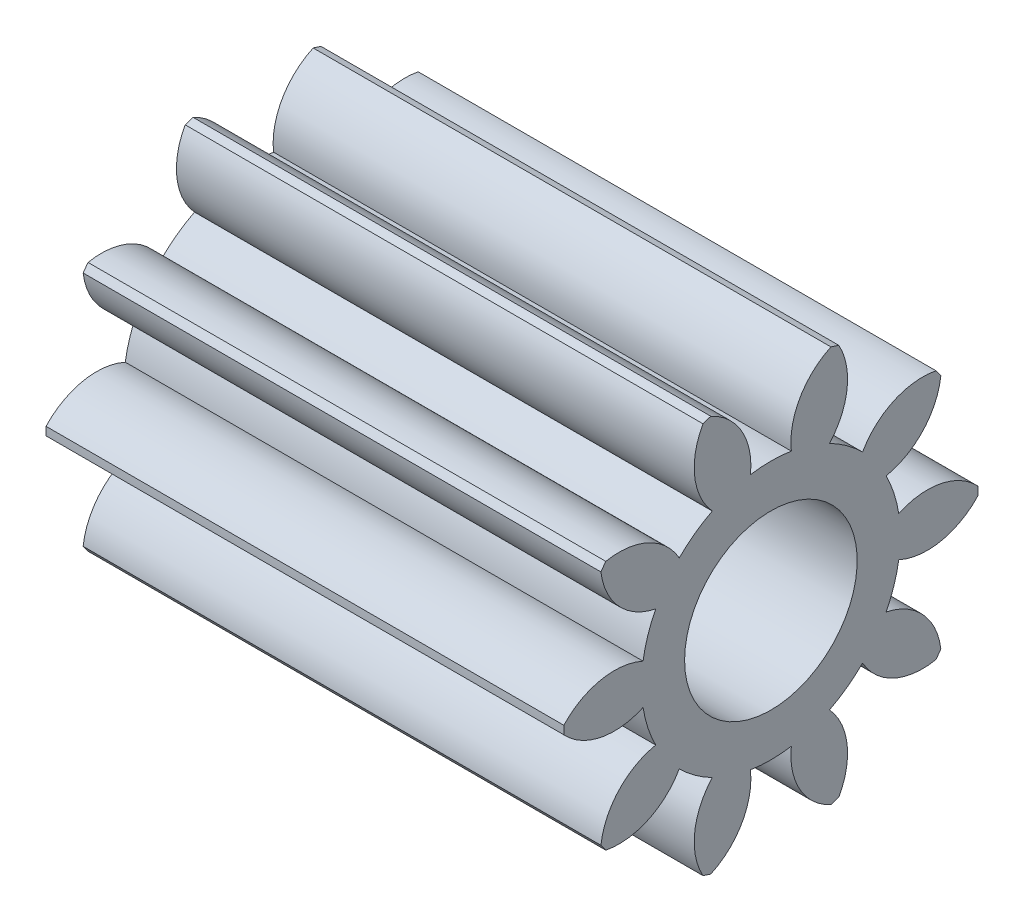
SolidWorks part; units mm, degrees
ref_plane "Plane1" through (0, 0, 0) normal (0, 0, 1) x (1, 0, 0)
ref_plane "Plane2" through (0, 0, 0) normal (0, 1, 0) x (1, 0, 0)
ref_plane "Plane3" through (0, 0, 0) normal (1, 0, 0) x (0, 0, -1)
other "Configuration Table"
sketch "HoldingSke" plane through (0, 0, 0) normal (0, 1, 0) x (1, 0, 0)
  line L0 (0, 0) -> (1.231, -0.2171)
  line L1 (-15, 0) -> (100, 0) construction
  line L2 (0, 0) -> (-2.1039, 2.3779)
  line L3 (0, 0) -> (-11.863, 4.5341)
  line L4 (0, 0) -> (8.5048, 1.4996)
  line L5 (0, 0) -> (-46.8476, -17.4728)
  line L6 (0, 0) -> (-9.9476, -6.7116)
  line L7 (-2.1039, 2.3779) -> (8.6586, 51.2059)
  line L8 (-76.2, 54.61) -> (-75.5, 54.61)
  line L9 (-71.009, 38.7566) -> (-53.1078, 45.2721)
  line L10 (-76.2, 71.12) -> (104.1128, 71.12)
  line L11 (0, 0) -> (-12, 0)
  line L12 (-76.2, 101.6) -> (-76.17, 101.6)
  line L13 (24.9733, 27.94) -> (52.9518, 28.4284)
  line L14 (24.9733, 27.94) -> (24.9743, 27.94)
  line L15 (24.9733, 27.94) -> (100.4006, 29.5858)
  line L16 (-63.627, -0.8) -> (-12.827, -0.8)
  circle A0 centre (0, 0) radius 2
  circle A1 centre (0, 0) radius 2.999
  circle A2 centre (0, 0) radius 37.5
  circle A3 centre (0, 0) radius 2
  dimension "MHD" = 5.998
  dimension "Hub_dia" = 75
  dimension "Bore" = 4
  dimension "MBD" = 4
  dimension "Num_teeth" = 10
  dimension "Pitch" = 1.25
  dimension "Overall_len" = 50
  dimension "Show_teeth" = 10
  dimension "Thickness" = 12
  dimension "OAL" = 50.0001
  dimension "T_dim" = 0.7
  dimension "Ap" = 20
  dimension "H" = 19.05
  dimension "Pitch_radius" = 180.3128
  dimension "Width" = 12
  dimension "Backlash" = 0.03
  dimension "Addendum_fac" = 1
  dimension "Dedendum_fac" = 1.25
  dimension "Clearance_fac" = 0.25
  dimension "Dedendum_add" = 0.001
  dimension "Module" = 0.8
sketch "BasProSke" plane through (0, 0, 0) normal (0, 1, 0) x (1, 0, 0)
  line L0 (-10, 0) -> (60, 0) construction
  line L1 (0, 0) -> (0, 4.8)
  line L2 (0, 0) -> (12, 0)
  line L3 (12, 0) -> (12, 4.8)
  line L4 (12, 4.8) -> (0, 4.8)
  dimension "Thickness" = 12
  dimension "Diameter" = 9.6
revolve "Base-Revolve" add sketch "BasProSke" angle 360 about L0
sketch "TooCutSke" plane through (0, 0, 0) normal (1, 0, 0) x (0, 0, -1)
  line L1 (0, 0) -> (0, 107) construction
  line L2 (0, 0) -> (-0.6781, 3.9421) construction
  line L3 (0, 0) -> (-2.4466, 7.5299) construction
  line L4 (-0.6781, 3.9421) -> (-1.2233, 3.765) construction
  arc A0 (0.4737, 2.9613) -> (-0.4737, 2.9613) centre (0, 0) ccw
  arc A1 (1.4269, 4.6096) -> (-1.4269, 4.6096) centre (0, 0) ccw
  circle A2 centre (0, 0) radius 4 construction
  circle A3 centre (0, 0) radius 3.7588 construction
  arc A4 (-0.4737, 2.9613) -> (-1.4269, 4.6096) centre (-2.0635, 3.1417) ccw
  arc A5 (1.4269, 4.6096) -> (0.4737, 2.9613) centre (2.0635, 3.1417) ccw
  dimension "Root_dia" = 5.998
  dimension "Overcut_dia" = 9.6508
  dimension "Pitch_dia" = 8
  dimension "Base_dia" = 7.5175
  dimension "Flank_rad" = 1.6
  dimension "Half_ang" = 18
  dimension "Half_CT" = 0.5732
extrude "ToothCut" cut sketch "TooCutSke" along normal through all
fillet "Breaks" [suppressed] radius 0.016
fillet "RootFillets" [suppressed] radius 0.201
pattern_circular "TeethCuts" count 10 every 36 about axis through (-10, 0, 0) along (1, 0, 0) of "ToothCut", "RootFillets", "Breaks"
sketch "HubNeaOneSke" plane through (0, 0, 0) normal (-1, 0, 0) x (0, 0, 1)
  circle A0 centre (0, 0) radius 2.999
  dimension "Diameter" = 5.998
extrude "HubNearOne" [suppressed] add sketch "HubNeaOneSke" along normal blind 38.0001
sketch "HubNeaBotSke" plane through (0, 0, 0) normal (-1, 0, 0) x (0, 0, 1)
  circle A0 centre (0, 0) radius 2.999
  dimension "Diameter" = 5.998
extrude "HubNearBoth" [suppressed] add sketch "HubNeaBotSke" along normal blind 19
ref_plane "FarPln" through (12, 0, 0) normal (1, 0, 0) x (0, 0, -1)
sketch "HubFarSke" plane through (12, 0, 0) normal (1, 0, 0) x (0, 0, -1)
  circle A0 centre (0, 0) radius 2.999
  dimension "Diameter" = 5.998
extrude "HubFar" [suppressed] add sketch "HubFarSke" along normal blind 19
sketch "BorSke" plane through (0, 0, 0) normal (1, 0, 0) x (0, 0, -1)
  circle A0 centre (0, 0) radius 2
  dimension "Diameter" = 4
extrude "Bore" cut sketch "BorSke" along normal mid plane 100.0001
sketch "KeySke" plane through (0, 0, 0) normal (1, 0, 0) x (0, 0, -1)
  line L0 (-0.8, 0) -> (-0.8, 2.7)
  line L1 (-0.8, 2.7) -> (0.8, 2.7)
  line L2 (0.8, 2.7) -> (0.8, 0)
  line L3 (0, 0) -> (0, 34) construction
  line L4 (-0.8, 0) -> (0.8, 0)
  dimension "Offset" = 2.7
  dimension "Width" = 1.6
extrude "Keyway" [suppressed] cut sketch "KeySke" along normal mid plane 100.0001
pattern_circular "Keyway2" [suppressed] count 2 every 90 about axis through (-10, 0, 0) along (1, 0, 0)
equation "' \"Module@HoldingSke\" = 6.35"
equation "' \"Num_teeth@HoldingSke\" = 12"
equation "' \"Ap@HoldingSke\" =  20"
equation "' \"Ap@HoldingSke\" = 20"
equation "' \"Width@HoldingSke\" = 0.5 * 25.4"
equation "' \"Hub_dia@HoldingSke\"= 1 * 25.4"
equation "' \"Hub_dia@HoldingSke\" = 1 * 25.4"
equation "' \"Overall_len@HoldingSke\" = 1.0 * 25.4"
equation "' \"Bore@HoldingSke\" = 0.75 * 25.4"
equation "' \"T_dim@HoldingSke\" = 0.1 * 25.4"
equation "' \"Width@KeySke\" = 0.25 * 25.4"
equation "' \"Show_teeth@HoldingSke\" = 13"
equation "' \"Backlash@HoldingSke\" = 0.009 * 25.4"
equation "' \"Addendum_fac@HoldingSke\" = 1.0"
equation "' \"Dedendum_fac@HoldingSke\" = 1.25"
equation "' \"Dedendum_add@HoldingSke\" = 0.00005 * 25.4"
equation "' \"Clearance_fac@HoldingSke\" = 0.25"
equation "\"Pitch@HoldingSke\" = 1 / \"Module@HoldingSke\""
equation "\"Overcut_dia@TooCutSke\" = (\"Num_teeth@HoldingSke\" + 2 * \"Addendum_fac@HoldingSke\") / \"Pitch@HoldingSke\" + 0.002 * 25.4"
equation "\"Pitch_dia@TooCutSke\" = \"Num_teeth@HoldingSke\" / \"Pitch@HoldingSke\""
equation "\"Base_dia@TooCutSke\" = \"Num_teeth@HoldingSke\" / \"Pitch@HoldingSke\" * cos((\"Ap@HoldingSke\"  * 3.14159265 / 180))"
equation "\"Root_dia@TooCutSke\" = (\"Num_teeth@HoldingSke\" + 2) / \"Pitch@HoldingSke\" - 2 * (\"Addendum_fac@HoldingSke\" + \"Dedendum_fac@HoldingSke\") / \"Pitch@HoldingSke\" - \"Dedendum_add@HoldingSke\" * 2"
equation "\"Half_ang@TooCutSke\" = 180 / \"Num_teeth@HoldingSke\""
equation "\"Half_CT@TooCutSke\" = \"Num_teeth@HoldingSke\" / \"Pitch@HoldingSke\" * sin((3.14159265 / 2 / \"Num_teeth@HoldingSke\")) / 2 - 7 * \"Backlash@HoldingSke\" / 4"
equation "\"Flank_rad@TooCutSke\" = \"Num_teeth@HoldingSke\" / \"Pitch@HoldingSke\" / 5"
equation "\"Radius@RootFillets\" = \"Clearance_fac@HoldingSke\" / \"Pitch@HoldingSke\" + \"Dedendum_add@HoldingSke\""
equation "\"Break_rad@Breaks\" = 0.02 / \"Pitch@HoldingSke\""
equation "\"Thickness@HoldingSke\" = \"Width@HoldingSke\""
equation "\"OAL@HoldingSke\" = \"Thickness@HoldingSke\""
equation "\"MHD@HoldingSke\" = (\"Num_teeth@HoldingSke\" + 2) / \"Pitch@HoldingSke\" - 2 * (\"Addendum_fac@HoldingSke\" + \"Dedendum_fac@HoldingSke\")  / \"Pitch@HoldingSke\" - \"Dedendum_add@HoldingSke\" * 2"
equation "\"MBD@HoldingSke\" = (\"Num_teeth@HoldingSke\" + 2) / \"Pitch@HoldingSke\" - 2 * (\"Addendum_fac@HoldingSke\" + \"Dedendum_fac@HoldingSke\")  / \"Pitch@HoldingSke\" - \"Dedendum_add@HoldingSke\" * 2 - 0.002 * 25.4"
equation "\"MHD@HoldingSke\" = ((sgn( \"MHD@HoldingSke\" - \"Hub_dia@HoldingSke\" )-1)*( \"MHD@HoldingSke\" - \"Hub_dia@HoldingSke\" ))/-2+ \"Hub_dia@HoldingSke\""
equation "\"MBD@HoldingSke\" = ((sgn( \"MBD@HoldingSke\" - \"Bore@HoldingSke\" )-1)*( \"MBD@HoldingSke\" - \"Bore@HoldingSke\" ))/-2+ \"Bore@HoldingSke\""
equation "\"OAL@HoldingSke\" = ((sgn( \"OAL@HoldingSke\" - \"Overall_len@HoldingSke\" )+1)*( \"OAL@HoldingSke\" - \"Overall_len@HoldingSke\" ))/2 + \"Overall_len@HoldingSke\" + 0.000002 * 25.4"
equation "\"Num_teeth@TeethCuts\" = int( \"Show_teeth@HoldingSke\" ) + 1"
equation "\"Num_teeth@TeethCuts\" = ((sgn( \"Num_teeth@TeethCuts\" - \"Num_teeth@HoldingSke\" )-1)*( \"Num_teeth@TeethCuts\" - \"Num_teeth@HoldingSke\" ))/-2+ \"Num_teeth@HoldingSke\""
equation "\"Num_teeth@TeethCuts\" = ((sgn( \"Num_teeth@TeethCuts\" - 2.0)+1)*( \"Num_teeth@TeethCuts\" - 2.0))/2 +2.0"
equation "\"Angle@TeethCuts\" = 360.0 / \"Num_teeth@HoldingSke\""
equation "\"Diameter@BasProSke\" = (\"Num_teeth@HoldingSke\" + 2 * \"Addendum_fac@HoldingSke\") / \"Pitch@HoldingSke\""
equation "\"Thickness@BasProSke\"  = \"Thickness@HoldingSke\""
equation "' \"Fillet_rad@BasProSke\" =  \"Thickness@HoldingSke\" * 0.05"
equation "' \"Fillet_rad@BasProSke\" = \"Thickness@HoldingSke\" * 0.05"
equation "\"MHD@HoldingSke\" = ((sgn( \"MHD@HoldingSke\" - \"Root_dia@TooCutSke\" )-1)*( \"MHD@HoldingSke\" - \"Root_dia@TooCutSke\" ))/-2+ \"Root_dia@TooCutSke\""
equation "\"Diameter@HubNeaOneSke\" = \"MHD@HoldingSke\""
equation "\"Length@HubNearOne\" = \"OAL@HoldingSke\" - \"Thickness@BasProSke\""
equation "\"Diameter@HubNeaBotSke\" = \"MHD@HoldingSke\""
equation "\"Length@HubNearBoth\" = ( \"OAL@HoldingSke\" - \"Thickness@BasProSke\" ) / 2.0"
equation "\"Thickness@FarPln\" = \"Thickness@BasProSke\""
equation "\"Diameter@HubFarSke\" = \"MHD@HoldingSke\""
equation "\"Length@HubFar\" = ( \"OAL@HoldingSke\" - \"Thickness@BasProSke\" ) / 2.0"
equation "\"Diameter@BorSke\" = \"MBD@HoldingSke\""
equation "\"D1@Bore\" = \"OAL@HoldingSke\" * 2.0"
equation "\"D1@Keyway\" = \"OAL@HoldingSke\" * 2.0"
equation "\"Offset@KeySke\" = \"T_dim@HoldingSke\" + \"MBD@HoldingSke\" / 2.0"
